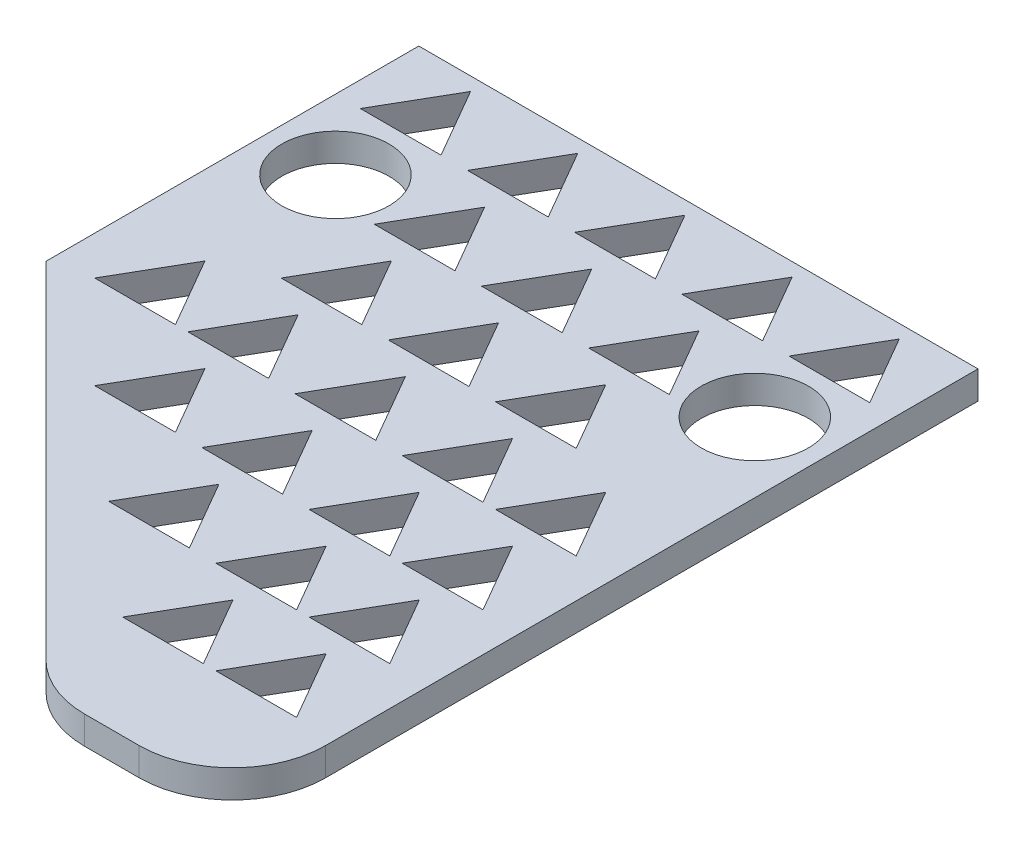
SolidWorks part; units mm, degrees
ref_plane "Front Plane" through (0, 0, 0) normal (0, 0, 1) x (1, 0, 0)
ref_plane "Top Plane" through (0, 0, 0) normal (0, 1, 0) x (1, 0, 0)
ref_plane "Right Plane" through (0, 0, 0) normal (1, 0, 0) x (0, 0, -1)
sketch "Sketch9" plane through (0, 0, 0) normal (0, 1, 0) x (1, 0, 0)
  line L1 (0, 0) -> (152.4, 0)
  line L2 (0, 0) -> (0, -203.2)
  line L3 (0, -203.2) -> (152.4, -203.2)
  line L4 (152.4, 0) -> (152.4, -203.2)
  dimension "D1" = 203.2
  dimension "D2" = 152.4
extrude "Boss-Extrude4" add sketch "Sketch9" along normal blind 7.62
sketch "Sketch10" plane through (0, 7.62, 0) normal (0, 1, 0) x (1, 0, 0)
  circle A2 centre (19.05, -41.7709) radius 14.605
  circle A3 centre (133.35, -41.7709) radius 14.605
  dimension "D5" = 29.21
  dimension "D6" = 29.21
extrude "Cut-Extrude4" cut sketch "Sketch10" against normal blind 7.62
sketch "Sketch11" plane through (0, 7.62, 0) normal (0, 1, 0) x (1, 0, 0)
  line L4 (0, -101.6) -> (101.6, -203.2)
  line L5 (0, 0) -> (0, -203.2) construction
  line L6 (0, -203.2) -> (152.4, -203.2) construction
  line L7 (101.6, -203.2) -> (0, -203.2)
  line L8 (0, -203.2) -> (0, -101.6)
  dimension "D1" = 101.6
  dimension "D2" = 101.6
extrude "Cut-Extrude5" cut sketch "Sketch11" against normal blind 7.62
fillet "Fillet2" radius 25.4 2 edges at (101.6, 3.81, 203.2) (152.4, 3.81, 203.2)
sketch "Sketch12" plane through (0, 7.62, 0) normal (0, 1, 0) x (1, 0, 0)
  line L0 (0, 0) -> (0, -101.6) construction
  line L1 (17.78, -3.6709) -> (6.7815, -22.7209)
  line L2 (6.7815, -22.7209) -> (28.7785, -22.7209)
  line L3 (28.7785, -22.7209) -> (17.78, -3.6709)
  line L4 (35.9915, -22.7209) -> (57.9885, -22.7209)
  line L5 (57.9885, -22.7209) -> (46.99, -3.6709)
  line L6 (46.99, -3.6709) -> (35.9915, -22.7209)
  line L7 (65.2015, -22.7209) -> (87.1985, -22.7209)
  line L8 (87.1985, -22.7209) -> (76.2, -3.6709)
  line L9 (76.2, -3.6709) -> (65.2015, -22.7209)
  line L10 (94.4115, -22.7209) -> (116.4085, -22.7209)
  line L11 (116.4085, -22.7209) -> (105.41, -3.6709)
  line L12 (105.41, -3.6709) -> (94.4115, -22.7209)
  line L13 (123.6215, -22.7209) -> (145.6185, -22.7209)
  line L14 (145.6185, -22.7209) -> (134.62, -3.6709)
  line L15 (134.62, -3.6709) -> (123.6215, -22.7209)
  line L16 (35.9915, -48.1209) -> (57.9885, -48.1209)
  line L17 (57.9885, -48.1209) -> (46.99, -29.0709)
  line L18 (46.99, -29.0709) -> (35.9915, -48.1209)
  line L19 (35.9915, -73.5209) -> (57.9885, -73.5209)
  line L20 (57.9885, -73.5209) -> (46.99, -54.4709)
  line L21 (46.99, -54.4709) -> (35.9915, -73.5209)
  line L22 (35.9915, -98.9209) -> (57.9885, -98.9209)
  line L23 (57.9885, -98.9209) -> (46.99, -79.8709)
  line L24 (46.99, -79.8709) -> (35.9915, -98.9209)
  line L25 (35.9915, -124.3209) -> (57.9885, -124.3209)
  line L26 (57.9885, -124.3209) -> (46.99, -105.2709)
  line L27 (46.99, -105.2709) -> (35.9915, -124.3209)
  line L28 (65.2015, -48.1209) -> (87.1985, -48.1209)
  line L29 (76.2, -29.0709) -> (65.2015, -48.1209)
  line L30 (87.1985, -48.1209) -> (76.2, -29.0709)
  line L31 (105.41, -29.0709) -> (94.4115, -48.1209)
  line L32 (94.4115, -48.1209) -> (116.4085, -48.1209)
  line L33 (116.4085, -48.1209) -> (105.41, -29.0709)
  line L34 (65.2015, -73.5209) -> (87.1985, -73.5209)
  line L35 (76.2, -54.4709) -> (65.2015, -73.5209)
  line L36 (87.1985, -73.5209) -> (76.2, -54.4709)
  line L37 (105.41, -54.4709) -> (94.4115, -73.5209)
  line L38 (94.4115, -73.5209) -> (116.4085, -73.5209)
  line L39 (116.4085, -73.5209) -> (105.41, -54.4709)
  line L40 (65.2015, -98.9209) -> (87.1985, -98.9209)
  line L41 (76.2, -79.8709) -> (65.2015, -98.9209)
  line L42 (87.1985, -98.9209) -> (76.2, -79.8709)
  line L43 (105.41, -79.8709) -> (94.4115, -98.9209)
  line L44 (94.4115, -98.9209) -> (116.4085, -98.9209)
  line L45 (116.4085, -98.9209) -> (105.41, -79.8709)
  line L46 (65.2015, -124.3209) -> (87.1985, -124.3209)
  line L47 (76.2, -105.2709) -> (65.2015, -124.3209)
  line L48 (87.1985, -124.3209) -> (76.2, -105.2709)
  line L49 (105.41, -105.2709) -> (94.4115, -124.3209)
  line L50 (94.4115, -124.3209) -> (116.4085, -124.3209)
  line L51 (116.4085, -124.3209) -> (105.41, -105.2709)
  line L52 (65.2015, -149.7209) -> (87.1985, -149.7209)
  line L53 (76.2, -130.6709) -> (65.2015, -149.7209)
  line L54 (87.1985, -149.7209) -> (76.2, -130.6709)
  line L55 (105.41, -130.6709) -> (94.4115, -149.7209)
  line L56 (94.4115, -149.7209) -> (116.4085, -149.7209)
  line L57 (116.4085, -149.7209) -> (105.41, -130.6709)
  line L58 (130.81, -79.8709) -> (119.8115, -98.9209)
  line L59 (119.8115, -98.9209) -> (141.8085, -98.9209)
  line L60 (141.8085, -98.9209) -> (130.81, -79.8709)
  line L61 (130.81, -105.2709) -> (119.8115, -124.3209)
  line L62 (119.8115, -124.3209) -> (141.8085, -124.3209)
  line L63 (141.8085, -124.3209) -> (130.81, -105.2709)
  line L64 (130.81, -130.6709) -> (119.8115, -149.7209)
  line L65 (119.8115, -149.7209) -> (141.8085, -149.7209)
  line L66 (141.8085, -149.7209) -> (130.81, -130.6709)
  line L67 (105.41, -156.0709) -> (94.4115, -175.1209)
  line L68 (94.4115, -175.1209) -> (116.4085, -175.1209)
  line L69 (116.4085, -175.1209) -> (105.41, -156.0709)
  line L70 (130.81, -156.0709) -> (119.8115, -175.1209)
  line L71 (119.8115, -175.1209) -> (141.8085, -175.1209)
  line L72 (141.8085, -175.1209) -> (130.81, -156.0709)
  line L73 (10.5915, -98.9209) -> (32.5885, -98.9209)
  line L74 (32.5885, -98.9209) -> (21.59, -79.8709)
  line L75 (21.59, -79.8709) -> (10.5915, -98.9209)
  circle A0 centre (17.78, -16.3709) radius 6.35 construction
  circle A1 centre (19.05, -41.7709) radius 14.605 construction
  dimension "D1" = 12.7
  dimension "D2" = 19.05
  dimension "D3" = 17.78
  dimension "D4" = 5
  dimension "D5" = 5
  dimension "D6" = 6
  dimension "D7" = 2
  dimension "D8" = 2
  dimension "D9" = 2
extrude "Cut-Extrude6" cut sketch "Sketch12" against normal blind 7.62
